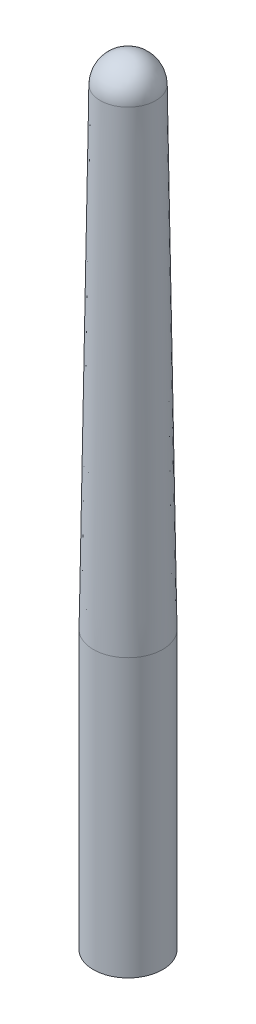
SolidWorks part; units mm, degrees
ref_plane "Front Plane" through (0, 0, 0) normal (0, 0, 1) x (1, 0, 0)
ref_plane "Top Plane" through (0, 0, 0) normal (0, 1, 0) x (1, 0, 0)
ref_plane "Right Plane" through (0, 0, 0) normal (1, 0, 0) x (0, 0, -1)
sketch "Sketch1" plane through (0, 0, 0) normal (0, 0, 1) x (1, 0, 0)
  line L0 (0, 0) -> (0, 112)
  line L1 (-3.9996, 108.0588) -> (-5, 40)
  line L2 (-5, 40) -> (-5, 0)
  line L3 (-5, 0) -> (0, 0)
  arc A0 (0, 112) -> (-3.9996, 108.0588) centre (0, 108) ccw
  dimension "D2" = 4
  dimension "D1" = 112
  dimension "D3" = 5
  dimension "D4" = 40
revolve "Revolve1" add sketch "Sketch1" angle 360 about L0
